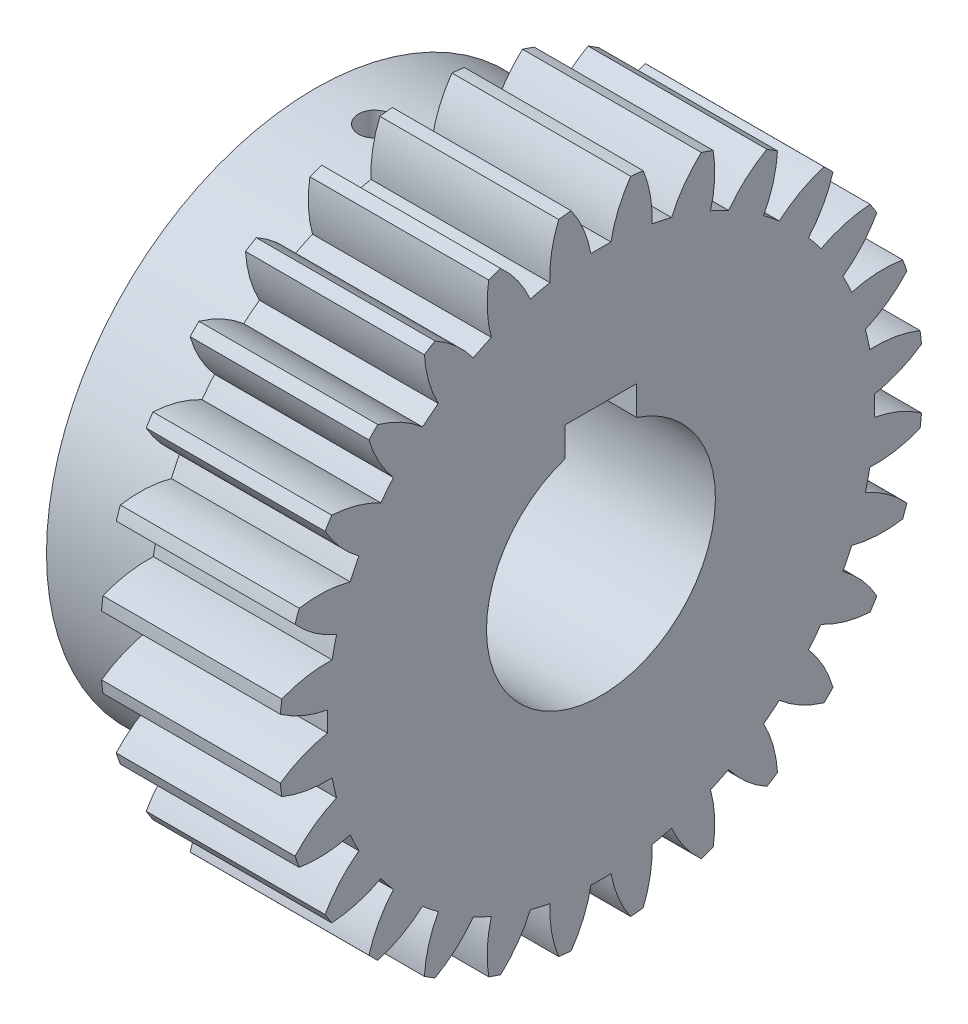
SolidWorks part; units mm, degrees
ref_plane "Plane1" through (0, 0, 0) normal (0, 0, 1) x (1, 0, 0)
ref_plane "Plane2" through (0, 0, 0) normal (0, 1, 0) x (1, 0, 0)
ref_plane "Plane3" through (0, 0, 0) normal (1, 0, 0) x (0, 0, -1)
sketch "HoldingSke" plane through (0, 0, 0) normal (0, 1, 0) x (1, 0, 0)
  line L0 (0, 0) -> (0.2943, -0.1565)
  line L1 (-15, 0) -> (100, 0) construction
  line L2 (0, 0) -> (-2.1039, 2.3779)
  line L3 (0, 0) -> (-11.863, 4.5341)
  line L4 (0, 0) -> (7.6251, 4.0544)
  line L5 (0, 0) -> (-37.4781, -13.9782)
  line L6 (0, 0) -> (-20.7241, -13.9826)
  line L7 (-2.1039, 2.3779) -> (6.5061, 41.4403)
  line L8 (-76.2, 54.61) -> (-72.9, 54.61)
  line L9 (-71.009, 38.7566) -> (-53.1078, 45.2721)
  line L10 (-76.2, 71.12) -> (104.1128, 71.12)
  line L11 (0, 0) -> (-25, 0)
  line L12 (-76.2, 101.6) -> (-76.093, 101.6)
  line L13 (24.9733, 27.94) -> (52.9518, 28.4284)
  line L14 (24.9733, 27.94) -> (24.9743, 27.94)
  line L15 (24.9733, 27.94) -> (100.4006, 29.5858)
  line L16 (-63.627, -3) -> (-12.827, -3)
  circle A0 centre (0, 0) radius 16
  circle A1 centre (0, 0) radius 37.5
  circle A2 centre (0, 0) radius 37.5
  circle A3 centre (0, 0) radius 16
  dimension "MHD" = 75
  dimension "Hub_dia" = 75
  dimension "Bore" = 32
  dimension "MBD" = 32
  dimension "Num_teeth" = 28
  dimension "Pitch" = 0.3333
  dimension "Overall_len" = 40
  dimension "Show_teeth" = 28
  dimension "Thickness" = 25
  dimension "OAL" = 40.0001
  dimension "T_dim" = 3.3
  dimension "Ap" = 20
  dimension "H" = 19.05
  dimension "Pitch_radius" = 180.3128
  dimension "Width" = 25
  dimension "Backlash" = 0.107
  dimension "Addendum_fac" = 1
  dimension "Dedendum_fac" = 1.25
  dimension "Clearance_fac" = 0.25
  dimension "Dedendum_add" = 0.001
  dimension "Module" = 3
sketch "BasProSke" plane through (0, 0, 0) normal (0, 1, 0) x (1, 0, 0)
  line L0 (-10, 0) -> (60, 0) construction
  line L1 (0, 0) -> (0, 45)
  line L2 (0, 0) -> (25, 0)
  line L3 (25, 0) -> (25, 45)
  line L4 (25, 45) -> (0, 45)
  dimension "Thickness" = 25
  dimension "Diameter" = 90
revolve "Base-Revolve" add sketch "BasProSke" angle 360 about L0
sketch "TooCutSke" plane through (0, 0, 0) normal (1, 0, 0) x (0, 0, -1)
  line L1 (0, 0) -> (0, 107) construction
  line L2 (0, 0) -> (-2.5422, 41.923) construction
  line L3 (0, 0) -> (-9.3925, 83.3606) construction
  line L4 (-2.5422, 41.923) -> (-4.6962, 41.6803) construction
  arc A0 (1.4032, 38.2233) -> (-1.4032, 38.2233) centre (0, 0) ccw
  arc A1 (4.1825, 44.8307) -> (-4.1825, 44.8307) centre (0, 0) ccw
  circle A2 centre (0, 0) radius 42 construction
  circle A3 centre (0, 0) radius 39.4671 construction
  arc A4 (-1.4032, 38.2233) -> (-4.1825, 44.8307) centre (-17.9222, 35.1632) ccw
  arc A5 (4.1825, 44.8307) -> (1.4032, 38.2233) centre (17.9222, 35.1632) ccw
  dimension "Root_dia" = 76.498
  dimension "Overcut_dia" = 90.0508
  dimension "Pitch_dia" = 84
  dimension "Base_dia" = 78.9342
  dimension "Flank_rad" = 16.8
  dimension "Half_ang" = 6.429
  dimension "Half_CT" = 2.1677
extrude "ToothCut" cut sketch "TooCutSke" along normal through all
fillet "Breaks" [suppressed] radius 0.06
fillet "RootFillets" [suppressed] radius 0.751
pattern_circular "TeethCuts" count 28 every 12.857 about axis through (-10, 0, 0) along (1, 0, 0) of "ToothCut", "RootFillets", "Breaks"
sketch "HubNeaOneSke" plane through (0, 0, 0) normal (-1, 0, 0) x (0, 0, 1)
  circle A0 centre (0, 0) radius 37.5
  dimension "Diameter" = 75
extrude "HubNearOne" add sketch "HubNeaOneSke" along normal blind 15.0001
sketch "HubNeaBotSke" plane through (0, 0, 0) normal (-1, 0, 0) x (0, 0, 1)
  circle A0 centre (0, 0) radius 37.5
  dimension "Diameter" = 75
extrude "HubNearBoth" [suppressed] add sketch "HubNeaBotSke" along normal blind 7.5
ref_plane "FarPln" through (25, 0, 0) normal (1, 0, 0) x (0, 0, -1)
sketch "HubFarSke" plane through (25, 0, 0) normal (1, 0, 0) x (0, 0, -1)
  circle A0 centre (0, 0) radius 37.5
  dimension "Diameter" = 75
extrude "HubFar" [suppressed] add sketch "HubFarSke" along normal blind 7.5
sketch "BorSke" plane through (0, 0, 0) normal (1, 0, 0) x (0, 0, -1)
  circle A0 centre (0, 0) radius 16
  dimension "Diameter" = 32
extrude "Bore" cut sketch "BorSke" along normal mid plane 80.0001
sketch "KeySke" plane through (0, 0, 0) normal (1, 0, 0) x (0, 0, -1)
  line L0 (-5, 0) -> (-5, 19.3)
  line L1 (-5, 19.3) -> (5, 19.3)
  line L2 (5, 19.3) -> (5, 0)
  line L3 (0, 0) -> (0, 34) construction
  line L4 (-5, 0) -> (5, 0)
  dimension "Offset" = 19.3
  dimension "Width" = 10
extrude "Keyway" cut sketch "KeySke" along normal mid plane 80.0001
pattern_circular "Keyway2" [suppressed] count 2 every 90 about axis through (-10, 0, 0) along (1, 0, 0)
sketch "Croquis1" plane through (0, 0, 0) normal (0, 1, 0) x (1, 0, 0)
  line L0 (60.4019, 0) -> (-37.2557, 0) construction
  circle A1 centre (-6.5, 0) radius 2.3813
  dimension "D1" = 4.7625
  dimension "D2" = 6.5
extrude "Cortar-Extruir1" cut sketch "Croquis1" against normal mid plane 100
sketch "Croquis2" plane through (-15.0001, 0, 0) normal (-1, 0, 0) x (0, 0, 1)
  line L0 (0, 44.5094) -> (0, -48.4532) construction
  line L1 (59.7802, 0) -> (-61.3433, 0) construction
  line L2 (-4.75, 29) -> (4.75, 29)
  line L3 (-4.75, 29) -> (-4.75, 25)
  line L4 (-4.75, 25) -> (4.75, 25)
  line L5 (4.75, 29) -> (4.75, 25)
  line L6 (4.75, -29) -> (4.75, -25)
  line L7 (-4.75, -29) -> (4.75, -29)
  line L8 (-4.75, -29) -> (-4.75, -25)
  line L9 (-4.75, -25) -> (4.75, -25)
  dimension "D1" = 4
  dimension "D2" = 9.5
  dimension "D3" = 25
extrude "Cortar-Extruir2" cut sketch "Croquis2" against normal blind 18
equation "' \"Module@HoldingSke\" = 6.35"
equation "' \"Num_teeth@HoldingSke\" = 12"
equation "' \"Ap@HoldingSke\" =  20"
equation "' \"Ap@HoldingSke\" = 20"
equation "' \"Width@HoldingSke\" = 0.5 * 25.4"
equation "' \"Hub_dia@HoldingSke\"= 1 * 25.4"
equation "' \"Hub_dia@HoldingSke\" = 1 * 25.4"
equation "' \"Overall_len@HoldingSke\" = 1.0 * 25.4"
equation "' \"Bore@HoldingSke\" = 0.75 * 25.4"
equation "' \"T_dim@HoldingSke\" = 0.1 * 25.4"
equation "' \"Width@KeySke\" = 0.25 * 25.4"
equation "' \"Show_teeth@HoldingSke\" = 13"
equation "' \"Backlash@HoldingSke\" = 0.009 * 25.4"
equation "' \"Addendum_fac@HoldingSke\" = 1.0"
equation "' \"Dedendum_fac@HoldingSke\" = 1.25"
equation "' \"Dedendum_add@HoldingSke\" = 0.00005 * 25.4"
equation "' \"Clearance_fac@HoldingSke\" = 0.25"
equation "\"Pitch@HoldingSke\" = 1 / \"Module@HoldingSke\""
equation "\"Overcut_dia@TooCutSke\" = (\"Num_teeth@HoldingSke\" + 2 * \"Addendum_fac@HoldingSke\") / \"Pitch@HoldingSke\" + 0.002 * 25.4"
equation "\"Pitch_dia@TooCutSke\" = \"Num_teeth@HoldingSke\" / \"Pitch@HoldingSke\""
equation "\"Base_dia@TooCutSke\" = \"Num_teeth@HoldingSke\" / \"Pitch@HoldingSke\" * cos((\"Ap@HoldingSke\"  * 3.14159265 / 180))"
equation "\"Root_dia@TooCutSke\" = (\"Num_teeth@HoldingSke\" + 2) / \"Pitch@HoldingSke\" - 2 * (\"Addendum_fac@HoldingSke\" + \"Dedendum_fac@HoldingSke\") / \"Pitch@HoldingSke\" - \"Dedendum_add@HoldingSke\" * 2"
equation "\"Half_ang@TooCutSke\" = 180 / \"Num_teeth@HoldingSke\""
equation "\"Half_CT@TooCutSke\" = \"Num_teeth@HoldingSke\" / \"Pitch@HoldingSke\" * sin((3.14159265 / 2 / \"Num_teeth@HoldingSke\")) / 2 - 7 * \"Backlash@HoldingSke\" / 4"
equation "\"Flank_rad@TooCutSke\" = \"Num_teeth@HoldingSke\" / \"Pitch@HoldingSke\" / 5"
equation "\"Radius@RootFillets\" = \"Clearance_fac@HoldingSke\" / \"Pitch@HoldingSke\" + \"Dedendum_add@HoldingSke\""
equation "\"Break_rad@Breaks\" = 0.02 / \"Pitch@HoldingSke\""
equation "\"Thickness@HoldingSke\" = \"Width@HoldingSke\""
equation "\"OAL@HoldingSke\" = \"Thickness@HoldingSke\""
equation "\"MHD@HoldingSke\" = (\"Num_teeth@HoldingSke\" + 2) / \"Pitch@HoldingSke\" - 2 * (\"Addendum_fac@HoldingSke\" + \"Dedendum_fac@HoldingSke\")  / \"Pitch@HoldingSke\" - \"Dedendum_add@HoldingSke\" * 2"
equation "\"MBD@HoldingSke\" = (\"Num_teeth@HoldingSke\" + 2) / \"Pitch@HoldingSke\" - 2 * (\"Addendum_fac@HoldingSke\" + \"Dedendum_fac@HoldingSke\")  / \"Pitch@HoldingSke\" - \"Dedendum_add@HoldingSke\" * 2 - 0.002 * 25.4"
equation "\"MHD@HoldingSke\" = ((sgn( \"MHD@HoldingSke\" - \"Hub_dia@HoldingSke\" )-1)*( \"MHD@HoldingSke\" - \"Hub_dia@HoldingSke\" ))/-2+ \"Hub_dia@HoldingSke\""
equation "\"MBD@HoldingSke\" = ((sgn( \"MBD@HoldingSke\" - \"Bore@HoldingSke\" )-1)*( \"MBD@HoldingSke\" - \"Bore@HoldingSke\" ))/-2+ \"Bore@HoldingSke\""
equation "\"OAL@HoldingSke\" = ((sgn( \"OAL@HoldingSke\" - \"Overall_len@HoldingSke\" )+1)*( \"OAL@HoldingSke\" - \"Overall_len@HoldingSke\" ))/2 + \"Overall_len@HoldingSke\" + 0.000002 * 25.4"
equation "\"Num_teeth@TeethCuts\" = int( \"Show_teeth@HoldingSke\" ) + 1"
equation "\"Num_teeth@TeethCuts\" = ((sgn( \"Num_teeth@TeethCuts\" - \"Num_teeth@HoldingSke\" )-1)*( \"Num_teeth@TeethCuts\" - \"Num_teeth@HoldingSke\" ))/-2+ \"Num_teeth@HoldingSke\""
equation "\"Num_teeth@TeethCuts\" = ((sgn( \"Num_teeth@TeethCuts\" - 2.0)+1)*( \"Num_teeth@TeethCuts\" - 2.0))/2 +2.0"
equation "\"Angle@TeethCuts\" = 360.0 / \"Num_teeth@HoldingSke\""
equation "\"Diameter@BasProSke\" = (\"Num_teeth@HoldingSke\" + 2 * \"Addendum_fac@HoldingSke\") / \"Pitch@HoldingSke\""
equation "\"Thickness@BasProSke\"  = \"Thickness@HoldingSke\""
equation "' \"Fillet_rad@BasProSke\" =  \"Thickness@HoldingSke\" * 0.05"
equation "' \"Fillet_rad@BasProSke\" = \"Thickness@HoldingSke\" * 0.05"
equation "\"MHD@HoldingSke\" = ((sgn( \"MHD@HoldingSke\" - \"Root_dia@TooCutSke\" )-1)*( \"MHD@HoldingSke\" - \"Root_dia@TooCutSke\" ))/-2+ \"Root_dia@TooCutSke\""
equation "\"Diameter@HubNeaOneSke\" = \"MHD@HoldingSke\""
equation "\"Length@HubNearOne\" = \"OAL@HoldingSke\" - \"Thickness@BasProSke\""
equation "\"Diameter@HubNeaBotSke\" = \"MHD@HoldingSke\""
equation "\"Length@HubNearBoth\" = ( \"OAL@HoldingSke\" - \"Thickness@BasProSke\" ) / 2.0"
equation "\"Thickness@FarPln\" = \"Thickness@BasProSke\""
equation "\"Diameter@HubFarSke\" = \"MHD@HoldingSke\""
equation "\"Length@HubFar\" = ( \"OAL@HoldingSke\" - \"Thickness@BasProSke\" ) / 2.0"
equation "\"Diameter@BorSke\" = \"MBD@HoldingSke\""
equation "\"D1@Bore\" = \"OAL@HoldingSke\" * 2.0"
equation "\"D1@Keyway\" = \"OAL@HoldingSke\" * 2.0"
equation "\"Offset@KeySke\" = \"T_dim@HoldingSke\" + \"MBD@HoldingSke\" / 2.0"
